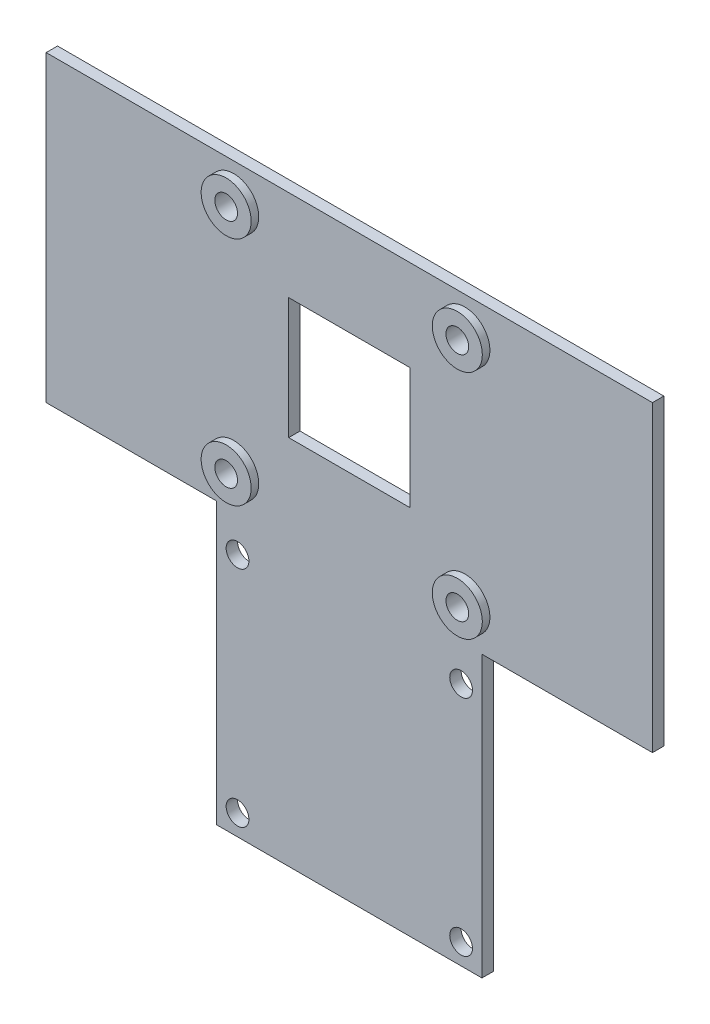
SolidWorks part; units mm, degrees
ref_plane "前视基准面" through (0, 0, 0) normal (0, 0, 1) x (1, 0, 0)
ref_plane "上视基准面" through (0, 0, 0) normal (0, 1, 0) x (1, 0, 0)
ref_plane "右视基准面" through (0, 0, 0) normal (1, 0, 0) x (0, 0, -1)
other "图形1"
sketch "草图2" plane through (0, 0, 0) normal (0, 0, 1) x (1, 0, 0)
  line L0 (-47.2291, 0.2568) -> (32.7709, 0.2568) construction
  line L1 (-47.2291, 20.2568) -> (32.7709, 20.2568)
  line L2 (-47.2291, 20.2568) -> (-47.2291, -19.7432)
  line L3 (-47.2291, -19.7432) -> (32.7709, -19.7432) construction
  line L4 (32.7709, 20.2568) -> (32.7709, -19.7432)
  line L5 (-7.2291, 20.2568) -> (-7.2291, -19.7432) construction
  line L6 (-7.2291, -7.7432) -> (0.7709, -7.7432)
  line L7 (0.7709, -7.7432) -> (0.7709, 8.2568)
  line L8 (0.7709, 8.2568) -> (-15.2291, 8.2568)
  line L9 (-15.2291, 8.2568) -> (-15.2291, -7.7432)
  line L10 (-15.2291, -7.7432) -> (-7.2291, -7.7432)
  line L11 (-47.2291, -19.7432) -> (-24.7291, -19.7432)
  line L12 (-24.7291, -19.7432) -> (-24.7291, -56.7432)
  line L13 (-24.7291, -56.7432) -> (10.2709, -56.7432)
  line L14 (10.2709, -56.7432) -> (10.2709, -19.7432)
  line L15 (10.2709, -19.7432) -> (32.7709, -19.7432)
  line L16 (-7.2291, -19.7432) -> (-7.2291, -54.7432) construction
  line L17 (-24.7291, -39.2432) -> (10.2709, -39.2432) construction
  circle A0 centre (-22.4791, 15.5068) radius 1.5
  circle A1 centre (8.0209, 15.5068) radius 1.5
  circle A2 centre (8.0209, -14.9932) radius 1.5
  circle A3 centre (-22.4791, -14.9932) radius 1.5
  circle A4 centre (-21.9791, -24.4932) radius 1.5
  circle A5 centre (7.5209, -24.4932) radius 1.5
  circle A6 centre (-21.9791, -53.9932) radius 1.5
  circle A7 centre (7.5209, -53.9932) radius 1.5
  point P35 (7.5209, -24.4932)
  point P37 (7.5209, -53.9932)
  dimension "D1" = 15.25
  dimension "D3" = 8
  dimension "D5" = 40
  dimension "D7" = 16
  dimension "D2" = 15.25
  dimension "D4" = 8
  dimension "D6" = 80
  dimension "D8" = 8
  dimension "D9" = 17.5
  dimension "D10" = 17.5
  dimension "D11" = 37
  dimension "D12" = 14.75
  dimension "D13" = 14.75
  dimension "D14" = 14.75
  dimension "D15" = 14.75
  dimension "D16" = 17.5
extrude "凸台-拉伸1" add sketch "草图2" along normal blind 1.5
sketch "草图3" plane through (0, 0, 1.5) normal (0, 0, 1) x (1, 0, 0)
  circle A0 centre (-22.4791, 15.5068) radius 1.5
  circle A1 centre (8.0209, 15.5068) radius 1.5
  circle A2 centre (8.0209, -14.9932) radius 1.5
  circle A3 centre (-22.4791, -14.9932) radius 1.5
  circle A4 centre (-22.4791, 15.5068) radius 3.3
  circle A5 centre (8.0209, 15.5068) radius 3.3
  circle A6 centre (-22.4791, -14.9932) radius 3.3
  circle A7 centre (8.0209, -14.9932) radius 3.3
extrude "凸台-拉伸2" add sketch "草图3" along normal blind 1
